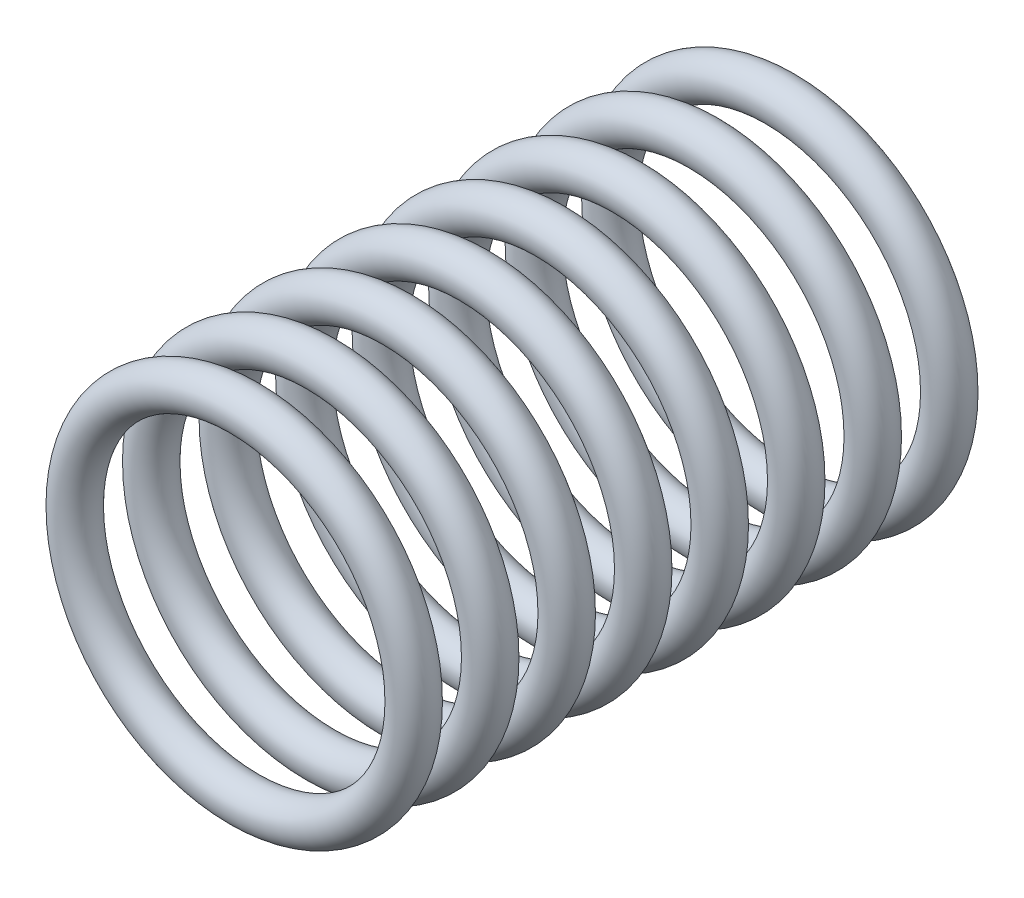
SolidWorks part; units mm, degrees
ref_plane "前视基准面" through (0, 0, 0) normal (0, 0, 1) x (1, 0, 0)
ref_plane "上视基准面" through (0, 0, 0) normal (0, 1, 0) x (1, 0, 0)
ref_plane "右视基准面" through (0, 0, 0) normal (1, 0, 0) x (0, 0, -1)
other "Configuration Table"
sketch "草图1" plane through (0, 0, 0) normal (0, 1, 0) x (1, 0, 0)
  line L0 (0, 0) -> (0, -17) construction
  circle A0 centre (5, -0.6) radius 0.6
  circle A1 centre (5, -2.8571) radius 0.6
  circle A2 centre (5, -5.1143) radius 0.6
  circle A3 centre (5, -7.3714) radius 0.6
  circle A4 centre (5, -9.6286) radius 0.6
  circle A5 centre (5, -11.8857) radius 0.6
  circle A6 centre (5, -14.1429) radius 0.6
  circle A7 centre (5, -16.4) radius 0.6
revolve "旋转1" add sketch "草图1" angle 360 about L0
